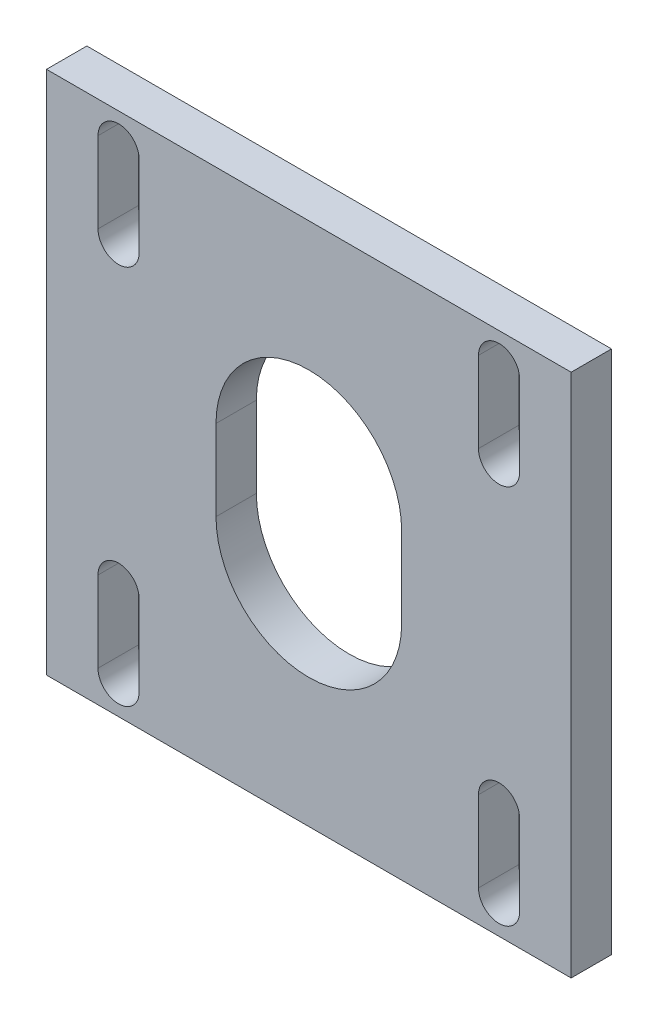
SolidWorks part; units mm, degrees
ref_plane "Front Plane" through (0, 0, 0) normal (0, 0, 1) x (1, 0, 0)
ref_plane "Top Plane" through (0, 0, 0) normal (0, 1, 0) x (1, 0, 0)
ref_plane "Right Plane" through (0, 0, 0) normal (1, 0, 0) x (0, 0, -1)
sketch "Sketch1" plane through (0, 0, 0) normal (0, 0, 1) x (1, 0, 0)
  line L2 (0, 0) -> (0, -65)
  line L3 (0, -65) -> (65, -65)
  line L9 (65, -65) -> (65, 0)
  line L10 (0, 0) -> (65, 0)
  line L11 (8.93, -8.93) -> (56.07, -8.93) construction
  line L12 (32.5, 0) -> (32.5, -65) construction
  line L13 (0, -32.5) -> (65, -32.5) construction
  line L14 (8.93, -3.93) -> (8.93, -13.93) construction
  line L15 (56.07, -56.07) -> (56.07, -8.93) construction
  line L16 (11.48, -3.93) -> (11.48, -13.93)
  line L17 (6.38, -3.93) -> (6.38, -13.93)
  line L18 (56.07, -3.93) -> (56.07, -13.93) construction
  line L19 (53.52, -3.93) -> (53.52, -13.93)
  line L20 (58.62, -3.93) -> (58.62, -13.93)
  line L21 (8.93, -61.07) -> (8.93, -51.07) construction
  line L22 (11.48, -61.07) -> (11.48, -51.07)
  line L23 (6.38, -61.07) -> (6.38, -51.07)
  line L24 (56.07, -61.07) -> (56.07, -51.07) construction
  line L25 (53.52, -61.07) -> (53.52, -51.07)
  line L26 (58.62, -61.07) -> (58.62, -51.07)
  arc A8 (11.48, -3.93) -> (6.38, -3.93) centre (8.93, -3.93) ccw
  arc A9 (6.38, -13.93) -> (11.48, -13.93) centre (8.93, -13.93) ccw
  arc A10 (53.52, -3.93) -> (58.62, -3.93) centre (56.07, -3.93) cw
  arc A11 (58.62, -13.93) -> (53.52, -13.93) centre (56.07, -13.93) cw
  arc A12 (11.48, -61.07) -> (6.38, -61.07) centre (8.93, -61.07) cw
  arc A13 (6.38, -51.07) -> (11.48, -51.07) centre (8.93, -51.07) cw
  arc A14 (53.52, -61.07) -> (58.62, -61.07) centre (56.07, -61.07) ccw
  arc A15 (58.62, -51.07) -> (53.52, -51.07) centre (56.07, -51.07) ccw
  point P16 (32.5, -8.93)
  point P17 (56.07, -32.5)
  point P20 (8.93, -8.93)
  point P21 (65, -65)
  point P26 (0, 0)
  point P29 (65, 0)
  point P31 (56.07, -8.93)
  point P37 (8.93, -56.07)
  point P44 (56.07, -56.07)
  dimension "D6" = 10
  dimension "D1" = 65
  dimension "D2" = 65
extrude "Boss-Extrude1" add sketch "Sketch1" along normal blind 5
sketch "Sketch2" plane through (0, 0, 5) normal (0, 0, 1) x (1, 0, 0)
  line L3 (32.5, -27.5) -> (32.5, -37.5) construction
  line L4 (44, -27.5) -> (44, -37.5)
  line L5 (21, -27.5) -> (21, -37.5)
  line L6 (0, 0) -> (0, -65) construction
  line L7 (65, 0) -> (0, 0) construction
  arc A1 (44, -27.5) -> (21, -27.5) centre (32.5, -27.5) ccw
  arc A2 (21, -37.5) -> (44, -37.5) centre (32.5, -37.5) ccw
  point P5 (32.5, -32.5)
  point P7 (0, -32.5)
  point P10 (32.5, 0)
  dimension "D1" = 10
  dimension "D2" = 11.5
extrude "Cut-Extrude2" cut sketch "Sketch2" against normal up to next
